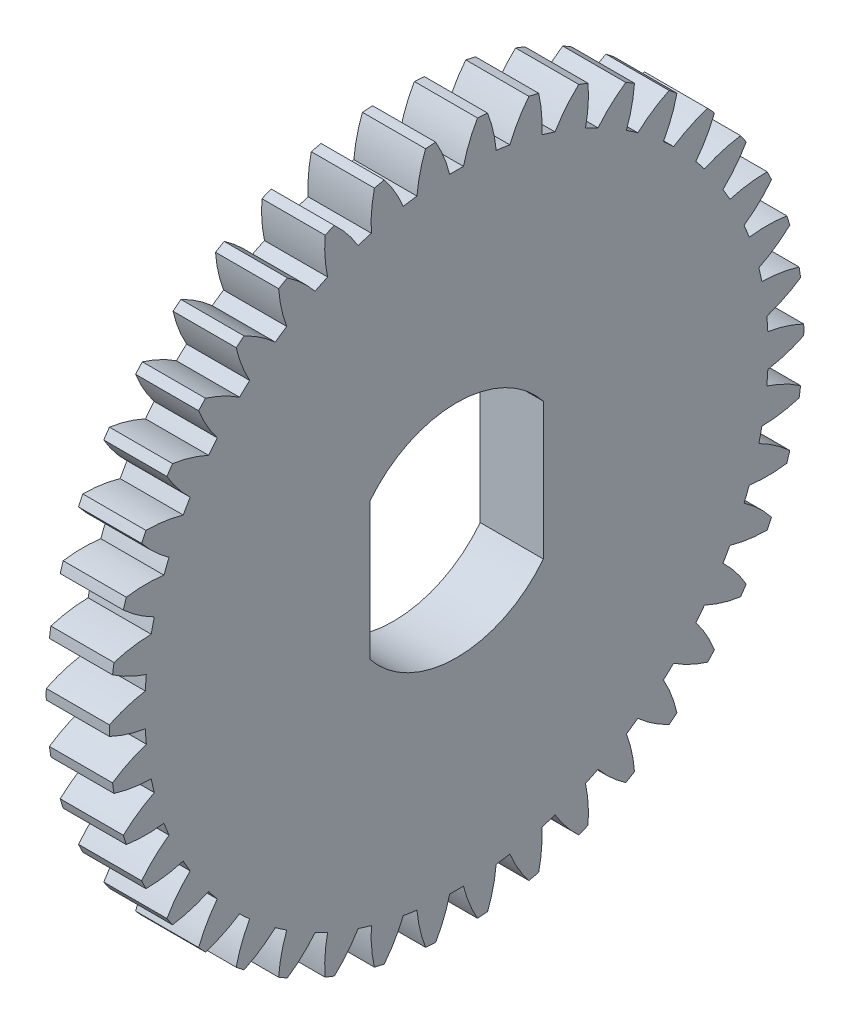
SolidWorks part; units mm, degrees
ref_plane "Plane1" through (0, 0, 0) normal (0, 0, 1) x (1, 0, 0)
ref_plane "Plane2" through (0, 0, 0) normal (0, 1, 0) x (1, 0, 0)
ref_plane "Plane3" through (0, 0, 0) normal (1, 0, 0) x (0, 0, -1)
sketch "HoldingSke" plane through (0, 0, 0) normal (0, 1, 0) x (1, 0, 0)
  line L0 (0, 0) -> (0.3716, -0.3346)
  line L1 (-15, 0) -> (100, 0) construction
  line L2 (0, 0) -> (-2.1039, 2.3779)
  line L3 (0, 0) -> (-11.863, 4.5341)
  line L4 (0, 0) -> (6.4178, 5.7786)
  line L5 (0, 0) -> (-46.8476, -17.4728)
  line L6 (0, 0) -> (-6.6317, -4.4744)
  line L7 (-2.1039, 2.3779) -> (8.6586, 51.2059)
  line L8 (-76.2, 54.61) -> (-73.9, 54.61)
  line L9 (-71.009, 38.7566) -> (-53.1078, 45.2721)
  line L10 (-76.2, 71.12) -> (104.1128, 71.12)
  line L11 (0, 0) -> (-8, 0)
  line L12 (-76.2, 101.6) -> (-76.133, 101.6)
  line L13 (24.9733, 27.94) -> (52.9518, 28.4284)
  line L14 (24.9733, 27.94) -> (24.9743, 27.94)
  line L15 (24.9733, 27.94) -> (100.4006, 29.5858)
  line L16 (-63.627, -2) -> (-12.827, -2)
  circle A0 centre (0, 0) radius 7
  circle A1 centre (0, 0) radius 37.5
  circle A2 centre (0, 0) radius 37.5
  circle A3 centre (0, 0) radius 7
  dimension "MHD" = 75
  dimension "Hub_dia" = 75
  dimension "Bore" = 14
  dimension "MBD" = 14
  dimension "Num_teeth" = 42
  dimension "Pitch" = 0.5
  dimension "Overall_len" = 50
  dimension "Show_teeth" = 42
  dimension "Thickness" = 8
  dimension "OAL" = 50.0001
  dimension "T_dim" = 2.3
  dimension "Ap" = 20
  dimension "H" = 19.05
  dimension "Pitch_radius" = 180.3128
  dimension "Width" = 8
  dimension "Backlash" = 0.067
  dimension "Addendum_fac" = 1
  dimension "Dedendum_fac" = 1.25
  dimension "Clearance_fac" = 0.25
  dimension "Dedendum_add" = 0.001
  dimension "Module" = 2
sketch "BasProSke" plane through (0, 0, 0) normal (0, 1, 0) x (1, 0, 0)
  line L0 (-10, 0) -> (60, 0) construction
  line L1 (0, 0) -> (0, 44)
  line L2 (0, 0) -> (8, 0)
  line L3 (8, 0) -> (8, 44)
  line L4 (8, 44) -> (0, 44)
  dimension "Thickness" = 8
  dimension "Diameter" = 88
revolve "Base-Revolve" add sketch "BasProSke" angle 360 about L0
sketch "TooCutSke" plane through (0, 0, 0) normal (1, 0, 0) x (0, 0, -1)
  line L1 (0, 0) -> (0, 107) construction
  line L2 (0, 0) -> (-1.6877, 41.9661) construction
  line L3 (0, 0) -> (-6.2736, 83.715) construction
  line L4 (-1.6877, 41.9661) -> (-3.1368, 41.8575) construction
  arc A0 (0.8776, 39.4892) -> (-0.8776, 39.4892) centre (0, 0) ccw
  arc A1 (2.6666, 43.9446) -> (-2.6666, 43.9446) centre (0, 0) ccw
  circle A2 centre (0, 0) radius 42 construction
  circle A3 centre (0, 0) radius 39.4671 construction
  arc A4 (-0.8776, 39.4892) -> (-2.6666, 43.9446) centre (-17.2022, 35.5209) ccw
  arc A5 (2.6666, 43.9446) -> (0.8776, 39.4892) centre (17.2022, 35.5209) ccw
  dimension "Root_dia" = 78.998
  dimension "Overcut_dia" = 88.0508
  dimension "Pitch_dia" = 84
  dimension "Base_dia" = 78.9342
  dimension "Flank_rad" = 16.8
  dimension "Half_ang" = 4.286
  dimension "Half_CT" = 1.4532
extrude "ToothCut" cut sketch "TooCutSke" along normal through all
fillet "Breaks" [suppressed] radius 0.04
fillet "RootFillets" [suppressed] radius 0.501
pattern_circular "TeethCuts" count 42 every 8.571 about axis through (-10, 0, 0) along (1, 0, 0) of "ToothCut", "RootFillets", "Breaks"
sketch "HubNeaOneSke" plane through (0, 0, 0) normal (-1, 0, 0) x (0, 0, 1)
  circle A0 centre (0, 0) radius 37.5
  dimension "Diameter" = 75
extrude "HubNearOne" [suppressed] add sketch "HubNeaOneSke" along normal blind 42.0001
sketch "HubNeaBotSke" plane through (0, 0, 0) normal (-1, 0, 0) x (0, 0, 1)
  circle A0 centre (0, 0) radius 37.5
  dimension "Diameter" = 75
extrude "HubNearBoth" [suppressed] add sketch "HubNeaBotSke" along normal blind 21
ref_plane "FarPln" through (8, 0, 0) normal (1, 0, 0) x (0, 0, -1)
sketch "HubFarSke" plane through (8, 0, 0) normal (1, 0, 0) x (0, 0, -1)
  circle A0 centre (0, 0) radius 37.5
  dimension "Diameter" = 75
extrude "HubFar" [suppressed] add sketch "HubFarSke" along normal blind 21
sketch "BorSke" plane through (0, 0, 0) normal (1, 0, 0) x (0, 0, -1)
  circle A0 centre (0, 0) radius 7
  dimension "Diameter" = 14
extrude "Bore" cut sketch "BorSke" along normal mid plane 100.0001
sketch "KeySke" plane through (0, 0, 0) normal (1, 0, 0) x (0, 0, -1)
  line L0 (-2.5, 0) -> (-2.5, 9.3)
  line L1 (-2.5, 9.3) -> (2.5, 9.3)
  line L2 (2.5, 9.3) -> (2.5, 0)
  line L3 (0, 0) -> (0, 34) construction
  line L4 (-2.5, 0) -> (2.5, 0)
  dimension "Offset" = 9.3
  dimension "Width" = 5
extrude "Keyway" [suppressed] cut sketch "KeySke" along normal mid plane 100.0001
pattern_circular "Keyway2" [suppressed] count 2 every 90 about axis through (-10, 0, 0) along (1, 0, 0)
sketch "Sketch1" plane through (0, 0, 0) normal (-1, 0, 0) x (0, 0, 1)
  line L0 (-11, 8.6603) -> (-11, -8.6603)
  line L1 (11, 8.6603) -> (11, -8.6603)
  arc A1 (-11, -8.6603) -> (11, -8.6603) centre (0, 0) ccw
  arc A2 (11, 8.6603) -> (-11, 8.6603) centre (0, 0) ccw
  point P7 (22.0614, -15.2511)
  dimension "D2" = 11
  dimension "D1" = 11
extrude "Cut-Extrude2" cut sketch "Sketch1" against normal blind 10
equation "' \"Module@HoldingSke\" = 6.35"
equation "' \"Num_teeth@HoldingSke\" = 12"
equation "' \"Ap@HoldingSke\" =  20"
equation "' \"Ap@HoldingSke\" = 20"
equation "' \"Width@HoldingSke\" = 0.5 * 25.4"
equation "' \"Hub_dia@HoldingSke\"= 1 * 25.4"
equation "' \"Hub_dia@HoldingSke\" = 1 * 25.4"
equation "' \"Overall_len@HoldingSke\" = 1.0 * 25.4"
equation "' \"Bore@HoldingSke\" = 0.75 * 25.4"
equation "' \"T_dim@HoldingSke\" = 0.1 * 25.4"
equation "' \"Width@KeySke\" = 0.25 * 25.4"
equation "' \"Show_teeth@HoldingSke\" = 13"
equation "' \"Backlash@HoldingSke\" = 0.009 * 25.4"
equation "' \"Addendum_fac@HoldingSke\" = 1.0"
equation "' \"Dedendum_fac@HoldingSke\" = 1.25"
equation "' \"Dedendum_add@HoldingSke\" = 0.00005 * 25.4"
equation "' \"Clearance_fac@HoldingSke\" = 0.25"
equation "\"Pitch@HoldingSke\" = 1 / \"Module@HoldingSke\""
equation "\"Overcut_dia@TooCutSke\" = (\"Num_teeth@HoldingSke\" + 2 * \"Addendum_fac@HoldingSke\") / \"Pitch@HoldingSke\" + 0.002 * 25.4"
equation "\"Pitch_dia@TooCutSke\" = \"Num_teeth@HoldingSke\" / \"Pitch@HoldingSke\""
equation "\"Base_dia@TooCutSke\" = \"Num_teeth@HoldingSke\" / \"Pitch@HoldingSke\" * cos((\"Ap@HoldingSke\"  * 3.14159265 / 180))"
equation "\"Root_dia@TooCutSke\" = (\"Num_teeth@HoldingSke\" + 2) / \"Pitch@HoldingSke\" - 2 * (\"Addendum_fac@HoldingSke\" + \"Dedendum_fac@HoldingSke\") / \"Pitch@HoldingSke\" - \"Dedendum_add@HoldingSke\" * 2"
equation "\"Half_ang@TooCutSke\" = 180 / \"Num_teeth@HoldingSke\""
equation "\"Half_CT@TooCutSke\" = \"Num_teeth@HoldingSke\" / \"Pitch@HoldingSke\" * sin((3.14159265 / 2 / \"Num_teeth@HoldingSke\")) / 2 - 7 * \"Backlash@HoldingSke\" / 4"
equation "\"Flank_rad@TooCutSke\" = \"Num_teeth@HoldingSke\" / \"Pitch@HoldingSke\" / 5"
equation "\"Radius@RootFillets\" = \"Clearance_fac@HoldingSke\" / \"Pitch@HoldingSke\" + \"Dedendum_add@HoldingSke\""
equation "\"Break_rad@Breaks\" = 0.02 / \"Pitch@HoldingSke\""
equation "\"Thickness@HoldingSke\" = \"Width@HoldingSke\""
equation "\"OAL@HoldingSke\" = \"Thickness@HoldingSke\""
equation "\"MHD@HoldingSke\" = (\"Num_teeth@HoldingSke\" + 2) / \"Pitch@HoldingSke\" - 2 * (\"Addendum_fac@HoldingSke\" + \"Dedendum_fac@HoldingSke\")  / \"Pitch@HoldingSke\" - \"Dedendum_add@HoldingSke\" * 2"
equation "\"MBD@HoldingSke\" = (\"Num_teeth@HoldingSke\" + 2) / \"Pitch@HoldingSke\" - 2 * (\"Addendum_fac@HoldingSke\" + \"Dedendum_fac@HoldingSke\")  / \"Pitch@HoldingSke\" - \"Dedendum_add@HoldingSke\" * 2 - 0.002 * 25.4"
equation "\"MHD@HoldingSke\" = ((sgn( \"MHD@HoldingSke\" - \"Hub_dia@HoldingSke\" )-1)*( \"MHD@HoldingSke\" - \"Hub_dia@HoldingSke\" ))/-2+ \"Hub_dia@HoldingSke\""
equation "\"MBD@HoldingSke\" = ((sgn( \"MBD@HoldingSke\" - \"Bore@HoldingSke\" )-1)*( \"MBD@HoldingSke\" - \"Bore@HoldingSke\" ))/-2+ \"Bore@HoldingSke\""
equation "\"OAL@HoldingSke\" = ((sgn( \"OAL@HoldingSke\" - \"Overall_len@HoldingSke\" )+1)*( \"OAL@HoldingSke\" - \"Overall_len@HoldingSke\" ))/2 + \"Overall_len@HoldingSke\" + 0.000002 * 25.4"
equation "\"Num_teeth@TeethCuts\" = int( \"Show_teeth@HoldingSke\" ) + 1"
equation "\"Num_teeth@TeethCuts\" = ((sgn( \"Num_teeth@TeethCuts\" - \"Num_teeth@HoldingSke\" )-1)*( \"Num_teeth@TeethCuts\" - \"Num_teeth@HoldingSke\" ))/-2+ \"Num_teeth@HoldingSke\""
equation "\"Num_teeth@TeethCuts\" = ((sgn( \"Num_teeth@TeethCuts\" - 2.0)+1)*( \"Num_teeth@TeethCuts\" - 2.0))/2 +2.0"
equation "\"Angle@TeethCuts\" = 360.0 / \"Num_teeth@HoldingSke\""
equation "\"Diameter@BasProSke\" = (\"Num_teeth@HoldingSke\" + 2 * \"Addendum_fac@HoldingSke\") / \"Pitch@HoldingSke\""
equation "\"Thickness@BasProSke\"  = \"Thickness@HoldingSke\""
equation "' \"Fillet_rad@BasProSke\" =  \"Thickness@HoldingSke\" * 0.05"
equation "' \"Fillet_rad@BasProSke\" = \"Thickness@HoldingSke\" * 0.05"
equation "\"MHD@HoldingSke\" = ((sgn( \"MHD@HoldingSke\" - \"Root_dia@TooCutSke\" )-1)*( \"MHD@HoldingSke\" - \"Root_dia@TooCutSke\" ))/-2+ \"Root_dia@TooCutSke\""
equation "\"Diameter@HubNeaOneSke\" = \"MHD@HoldingSke\""
equation "\"Length@HubNearOne\" = \"OAL@HoldingSke\" - \"Thickness@BasProSke\""
equation "\"Diameter@HubNeaBotSke\" = \"MHD@HoldingSke\""
equation "\"Length@HubNearBoth\" = ( \"OAL@HoldingSke\" - \"Thickness@BasProSke\" ) / 2.0"
equation "\"Thickness@FarPln\" = \"Thickness@BasProSke\""
equation "\"Diameter@HubFarSke\" = \"MHD@HoldingSke\""
equation "\"Length@HubFar\" = ( \"OAL@HoldingSke\" - \"Thickness@BasProSke\" ) / 2.0"
equation "\"Diameter@BorSke\" = \"MBD@HoldingSke\""
equation "\"D1@Bore\" = \"OAL@HoldingSke\" * 2.0"
equation "\"D1@Keyway\" = \"OAL@HoldingSke\" * 2.0"
equation "\"Offset@KeySke\" = \"T_dim@HoldingSke\" + \"MBD@HoldingSke\" / 2.0"
